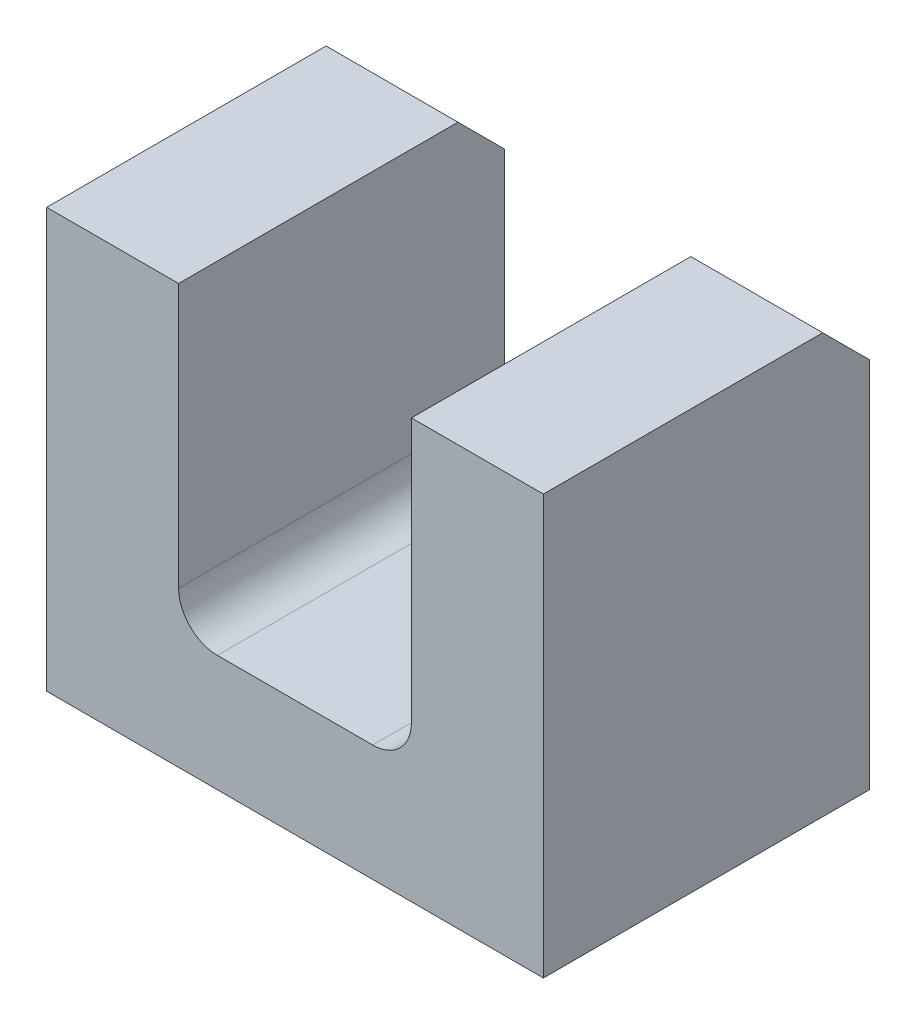
SolidWorks part; units mm, degrees
ref_plane "Front Plane" through (0, 0, 0) normal (0, 0, 1) x (1, 0, 0)
ref_plane "Top Plane" through (0, 0, 0) normal (0, 1, 0) x (1, 0, 0)
ref_plane "Right Plane" through (0, 0, 0) normal (1, 0, 0) x (0, 0, -1)
sketch "Sketch1" plane through (0, 0, 0) normal (0, 1, 0) x (1, 0, 0)
  line L1 (3.2, -2.1) -> (-3.2, -2.1)
  line L2 (3.2, -2.1) -> (3.2, 2.1)
  line L3 (3.2, 2.1) -> (-3.2, 2.1)
  line L4 (-3.2, -2.1) -> (-3.2, 2.1)
  line L5 (3.2, -2.1) -> (-3.2, 2.1) construction
  line L6 (3.2, 2.1) -> (-3.2, -2.1) construction
  point P0 (0, 0)
  dimension "D1" = 6.4
  dimension "D2" = 4.2
extrude "Boss-Extrude1" add sketch "Sketch1" along normal blind 5.4
sketch "Sketch2" plane through (0, 5.4, 0) normal (0, 1, 0) x (1, 0, 0)
  line L0 (3.2, 2.1) -> (-3.2, 2.1) construction
  line L1 (1.5, -2.1) -> (-1.5, -2.1)
  line L2 (1.5, -2.1) -> (1.5, 2.1)
  line L3 (1.5, 2.1) -> (-1.5, 2.1)
  line L4 (-1.5, -2.1) -> (-1.5, 2.1)
  line L5 (1.5, -2.1) -> (-1.5, 2.1) construction
  line L6 (1.5, 2.1) -> (-1.5, -2.1) construction
  point P0 (0, 0)
  dimension "D1" = 3
extrude "Cut-Extrude1" cut sketch "Sketch2" against normal blind 3.9
fillet "Fillet1" radius 0.5 2 edges at (1.5, 1.5, 0) (-1.5, 1.5, 0)
chamfer "Chamfer1" distance 0.6 angle 45 2 edges at (2.35, 5.4, -2.1) (-2.35, 5.4, -2.1)
